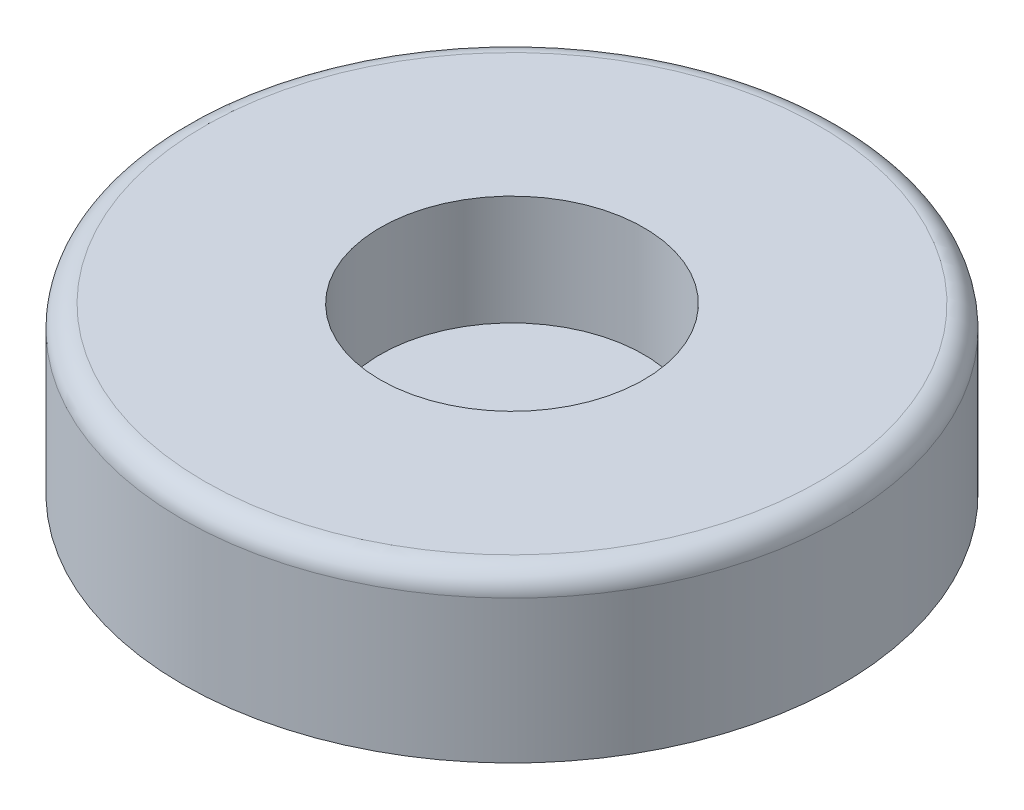
SolidWorks part; units mm, degrees
ref_plane "Front Plane" through (0, 0, 0) normal (0, 0, 1) x (1, 0, 0)
ref_plane "Top Plane" through (0, 0, 0) normal (0, 1, 0) x (1, 0, 0)
ref_plane "Right Plane" through (0, 0, 0) normal (1, 0, 0) x (0, 0, -1)
sketch "Sketch1" plane through (0, 0, 0) normal (0, 1, 0) x (1, 0, 0)
  circle A0 centre (0, 0) radius 30
  dimension "D1" = 60
extrude "Boss-Extrude1" add sketch "Sketch1" along normal blind 15
sketch "Sketch2" plane through (0, 15, 0) normal (0, 1, 0) x (1, 0, 0)
  circle A0 centre (0, 0) radius 12
  dimension "D1" = 24
extrude "Cut-Extrude1" cut sketch "Sketch2" against normal blind 10
fillet "Fillet1" radius 2 1 edges at (0, 15, 30)
